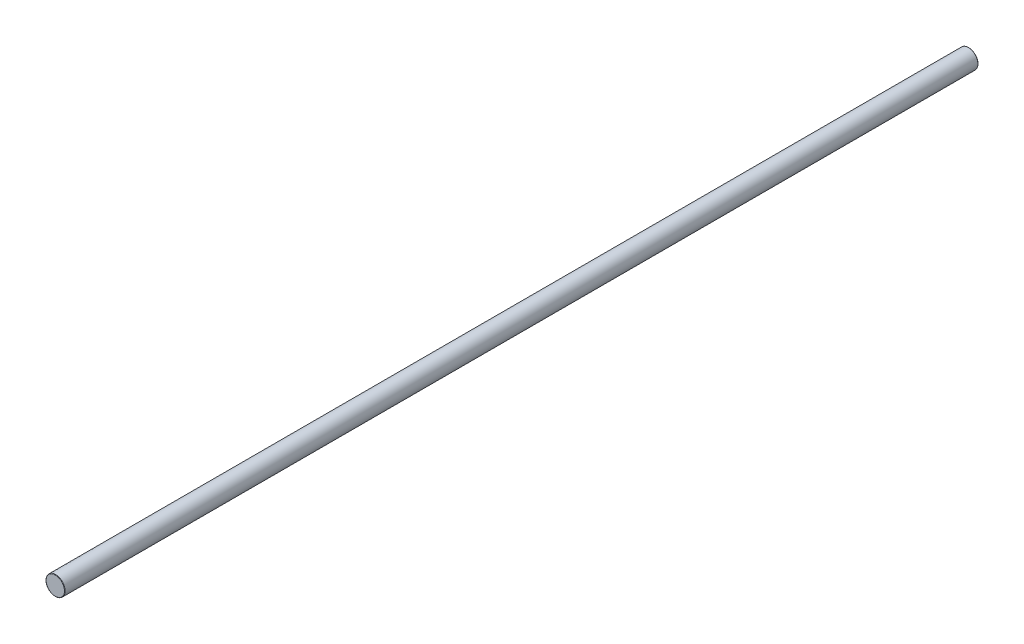
SolidWorks part; units mm, degrees
ref_plane "Front Plane" through (0, 0, 0) normal (0, 0, 1) x (1, 0, 0)
ref_plane "Top Plane" through (0, 0, 0) normal (0, 1, 0) x (1, 0, 0)
ref_plane "Right Plane" through (0, 0, 0) normal (1, 0, 0) x (0, 0, -1)
sketch "Sketch1" plane through (0, 0, 0) normal (0, 0, 1) x (1, 0, 0)
  circle A0 centre (0, 0) radius 6.35
  dimension "D1" = 12.7
extrude "Boss-Extrude1" add sketch "Sketch1" along normal blind 609.6
fillet "Fillet1" radius 0.25 2 edges at (6.35, 0, 0) (6.35, 0, 609.6)
